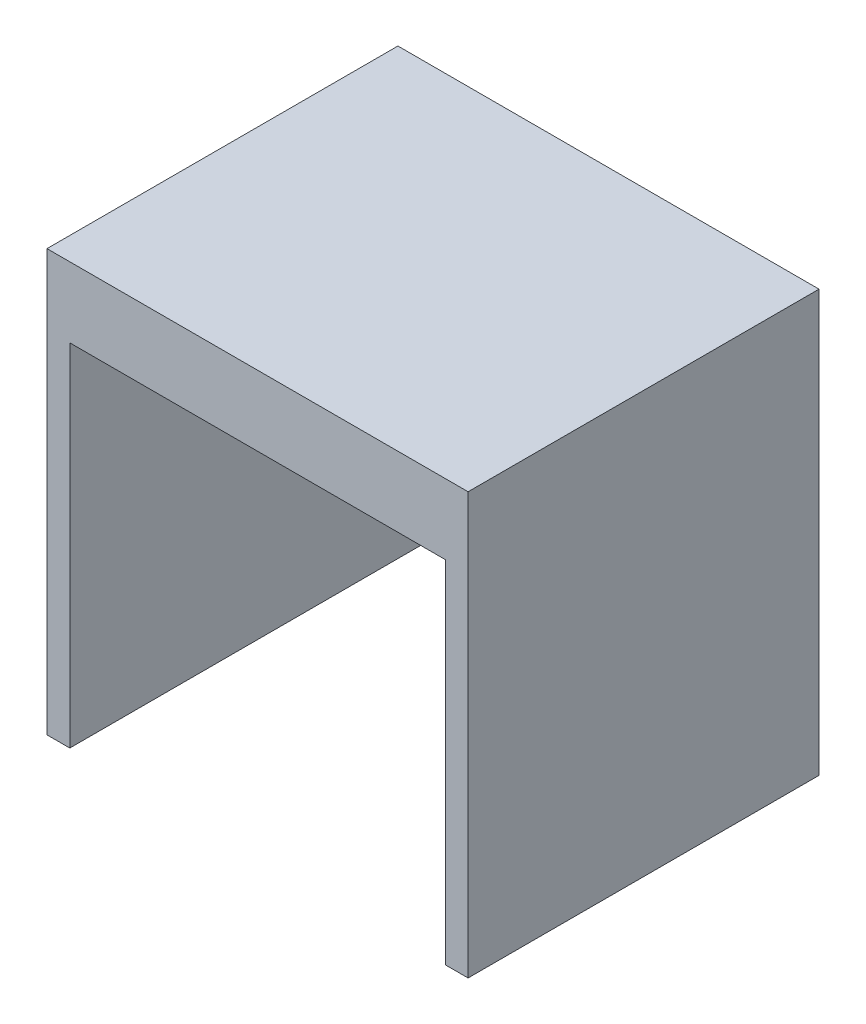
SolidWorks part; units mm, degrees
ref_plane "Front Plane" through (0, 0, 0) normal (0, 0, 1) x (1, 0, 0)
ref_plane "Top Plane" through (0, 0, 0) normal (0, 1, 0) x (1, 0, 0)
ref_plane "Right Plane" through (0, 0, 0) normal (1, 0, 0) x (0, 0, -1)
sketch "Sketch1" plane through (0, 0, 0) normal (0, 1, 0) x (1, 0, 0)
  line L1 (-60, 50) -> (60, 50)
  line L2 (-60, 50) -> (-60, -50)
  line L3 (-60, -50) -> (60, -50)
  line L4 (60, 50) -> (60, -50)
  line L5 (-60, 50) -> (60, -50) construction
  line L6 (-60, -50) -> (60, 50) construction
  point P0 (0, 0)
  dimension "D1" = 120
  dimension "D2" = 100
extrude "Boss-Extrude1" add sketch "Sketch1" along normal blind 120
sketch "Sketch2" plane through (0, 0, 0) normal (0, -1, 0) x (1, 0, 0)
  line L1 (-53.5, 60) -> (53.5, 60)
  line L2 (-53.5, 60) -> (-53.5, -60)
  line L3 (-53.5, -60) -> (53.5, -60)
  line L4 (53.5, 60) -> (53.5, -60)
  line L5 (-53.5, 60) -> (53.5, -60) construction
  line L6 (-53.5, -60) -> (53.5, 60) construction
  point P0 (0, 0)
  dimension "D1" = 107
  dimension "D2" = 120
extrude "Cut-Extrude1" cut sketch "Sketch2" against normal blind 100
sketch "Sketch4" plane through (0, 0, -50) normal (0, 0, -1) x (-1, 0, 0)
  line L1 (-38.5844, 115.7319) -> (46.4156, 115.7319)
  line L2 (-38.5844, 115.7319) -> (-38.5844, 102.7319)
  line L3 (-38.5844, 102.7319) -> (46.4156, 102.7319)
  line L4 (46.4156, 115.7319) -> (46.4156, 102.7319)
  line L5 (-38.5844, 115.7319) -> (46.4156, 102.7319) construction
  line L6 (-38.5844, 102.7319) -> (46.4156, 115.7319) construction
  point P0 (3.9156, 109.2319)
  dimension "D1" = 85
  dimension "D2" = 13
extrude "Cut-Extrude2" cut sketch "Sketch4" against normal blind 95
sketch "Sketch5" plane through (0, 0, -50) normal (0, 0, -1) x (-1, 0, 0)
  line L0 (-38.5844, 102.7319) -> (46.4156, 102.7319) construction
  line L1 (-36.8378, 102.7319) -> (42.7319, 102.7319)
  line L2 (-36.8378, 102.7319) -> (-36.8378, 100)
  line L3 (-36.8378, 100) -> (42.7319, 100)
  line L4 (42.7319, 102.7319) -> (42.7319, 100)
  line L5 (53.5, 100) -> (-53.5, 100) construction
extrude "Cut-Extrude3" cut sketch "Sketch5" against normal blind 40 from offset 50
